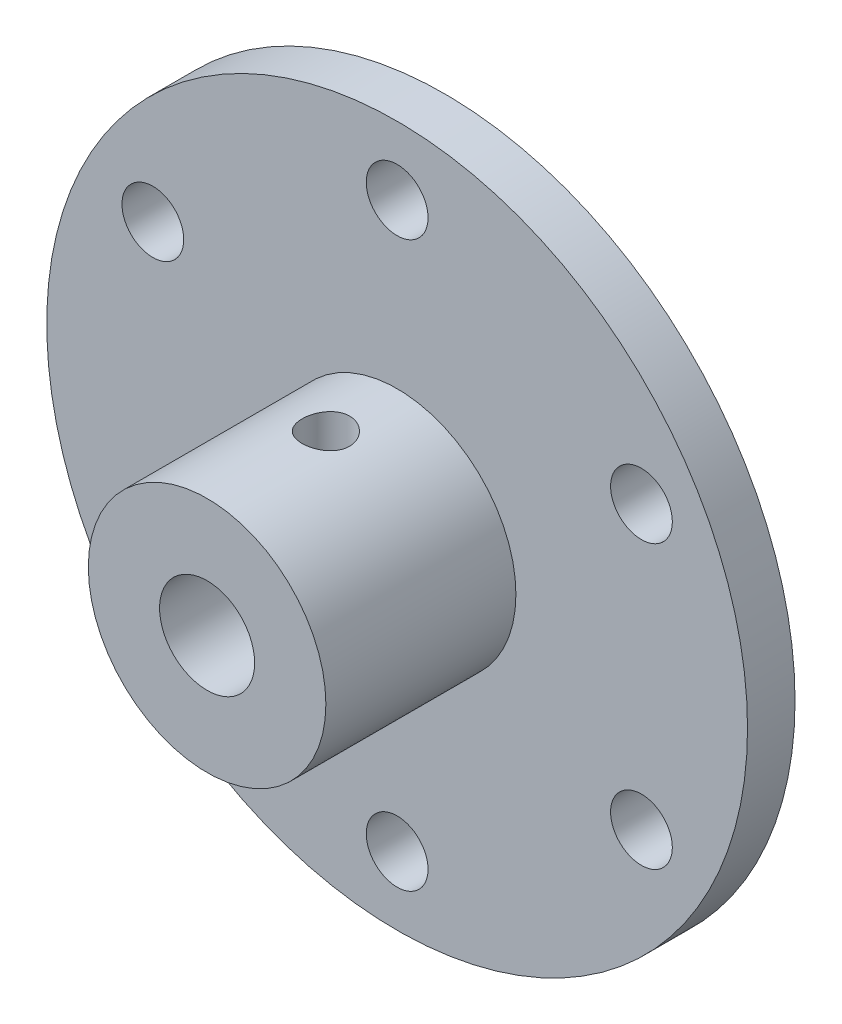
SolidWorks part; units mm, degrees
ref_plane "Front Plane" through (0, 0, 0) normal (0, 0, 1) x (1, 0, 0)
ref_plane "Top Plane" through (0, 0, 0) normal (0, 1, 0) x (1, 0, 0)
ref_plane "Right Plane" through (0, 0, 0) normal (1, 0, 0) x (0, 0, -1)
sketch "Sketch1" plane through (0, 0, 0) normal (0, 0, 1) x (1, 0, 0)
  circle A0 centre (0, 0) radius 29.5
  dimension "D1" = 59
extrude "Boss-Extrude1" add sketch "Sketch1" along normal blind 4
sketch "Sketch2" plane through (0, 0, 4) normal (0, 0, 1) x (1, 0, 0)
  circle A0 centre (0, 0) radius 10
  dimension "D1" = 20
extrude "Boss-Extrude2" add sketch "Sketch2" along normal blind 16
sketch "Sketch3" plane through (0, 0, 20) normal (0, 0, 1) x (1, 0, 0)
  circle A0 centre (0, 0) radius 4
  dimension "D1" = 8
extrude "Cut-Extrude1" cut sketch "Sketch3" against normal up to surface (20 mm away) up to face at (29.5, 0, 0)
sketch "Sketch4" plane through (0, 0, 4) normal (0, 0, 1) x (1, 0, 0)
  circle A0 centre (0, 0) radius 23.75 construction
  circle A1 centre (0, 23.75) radius 2.6
  circle A2 centre (20.5681, 11.875) radius 2.6
  circle A3 centre (20.5681, -11.875) radius 2.6
  circle A4 centre (0, -23.75) radius 2.6
  circle A5 centre (-20.5681, -11.875) radius 2.6
  circle A6 centre (-20.5681, 11.875) radius 2.6
  point P18 (0, 0)
  dimension "D1" = 47.5
  dimension "D2" = 5.2
  dimension "D3" = 6
extrude "Cut-Extrude2" cut sketch "Sketch4" against normal up to surface (4 mm away) up to face at (4, 0, 0)
sketch "Sketch5" plane through (0, 0, 0) normal (0, 1, 0) x (1, 0, 0)
  circle A0 centre (0, -10) radius 2
  dimension "D1" = 4
  dimension "D2" = 10
extrude "Cut-Extrude3" cut sketch "Sketch5" against normal through all both and the other way through all
